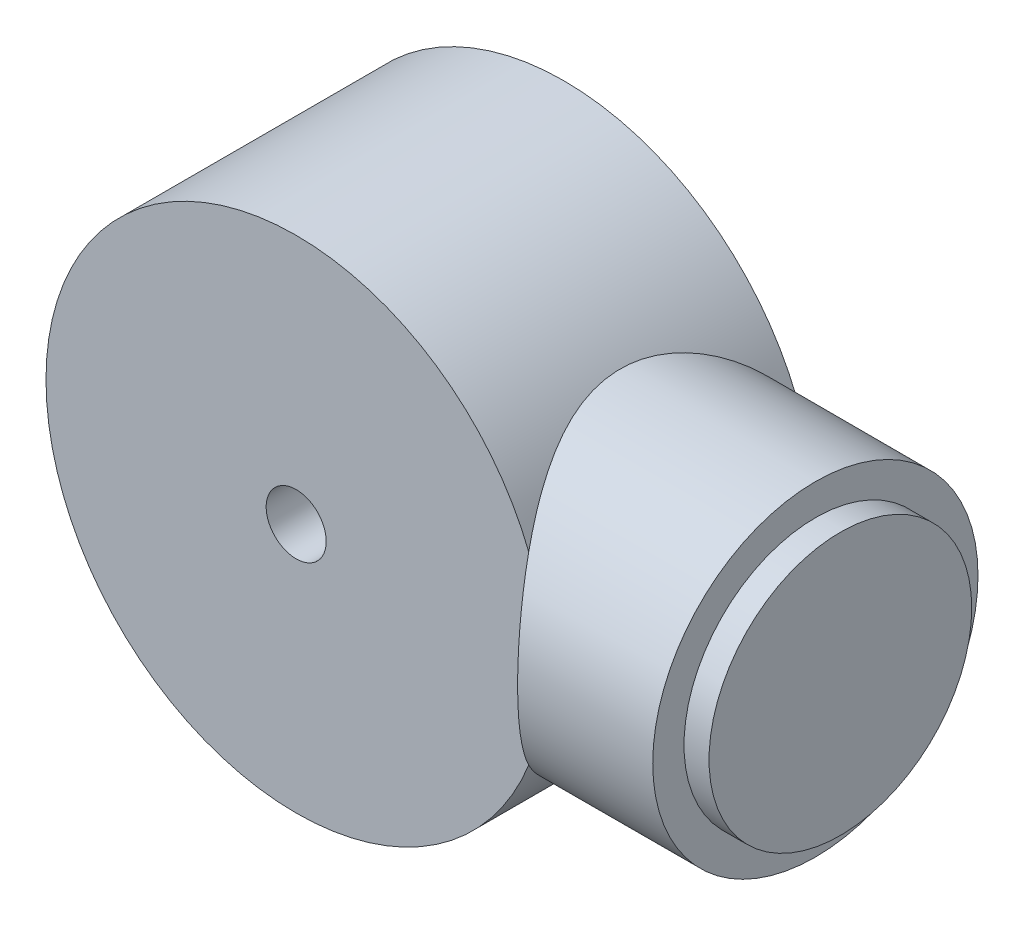
SolidWorks part; units mm, degrees
ref_plane "Plano frontal" through (0, 0, 0) normal (0, 0, 1) x (1, 0, 0)
ref_plane "Plano superior" through (0, 0, 0) normal (0, 1, 0) x (1, 0, 0)
ref_plane "Plano direito" through (0, 0, 0) normal (1, 0, 0) x (0, 0, -1)
sketch "Esboço1" plane through (0, 0, 0) normal (0, 0, 1) x (1, 0, 0)
  circle A0 centre (0, 0) radius 50
  dimension "D1" = 100
extrude "Ressalto-extrusão1" add sketch "Esboço1" along normal mid plane 53.5
ref_plane "Plano1" through (77, 0, 0) normal (1, 0, 0) x (0, 0, -1)
sketch "Esboço2" plane through (77, 0, 0) normal (1, 0, 0) x (0, 0, -1)
  circle A0 centre (0, 0) radius 32.5
  dimension "D1" = 65
extrude "Ressalto-extrusão3" add sketch "Esboço2" against normal up to surface (27 mm away) up to face at (50, 0, 26.75)
sketch "Esboço3" plane through (77, 0, 0) normal (1, 0, 0) x (0, 0, -1)
  circle A0 centre (0, 0) radius 26.25
  dimension "D1" = 52.5
extrude "Ressalto-extrusão4" add sketch "Esboço3" along normal blind 5
sketch "Esboço4" plane through (0, 0, 26.75) normal (0, 0, 1) x (1, 0, 0)
  circle A0 centre (0, 0) radius 6
  dimension "D1" = 12
extrude "Corte-extrusão1" cut sketch "Esboço4" against normal through all
